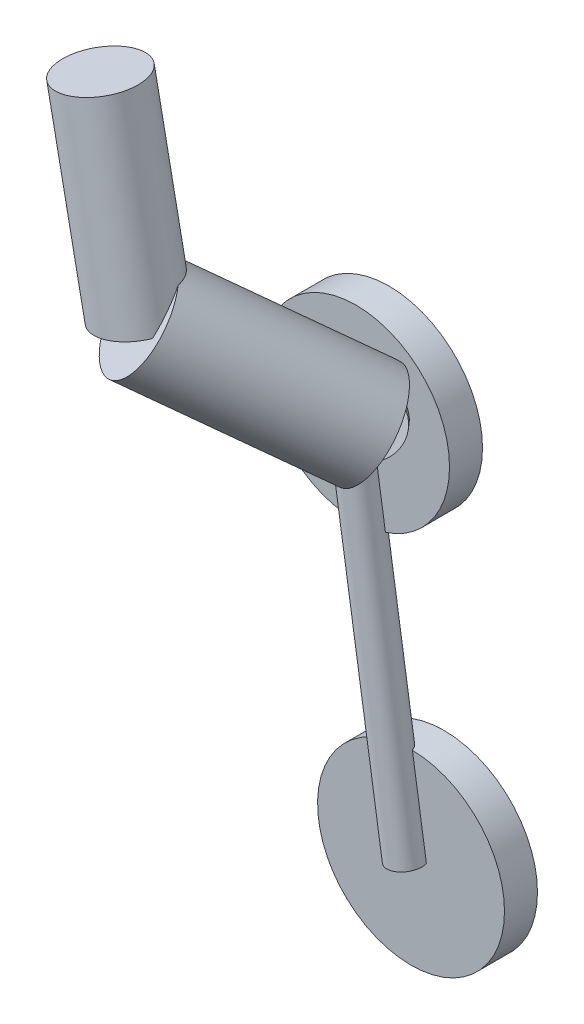
SolidWorks part; units mm, degrees
ref_plane "Alzado" through (0, 0, 0) normal (0, 0, 1) x (1, 0, 0)
ref_plane "Planta" through (0, 0, 0) normal (0, 1, 0) x (1, 0, 0)
ref_plane "Vista lateral" through (0, 0, 0) normal (1, 0, 0) x (0, 0, -1)
sketch3d "Sk_Patilla"
  line L0 (-425.1, 65, 76) -> (-418.1, 30, 76)
  dimension "D1" = 35.6931
sweep "Patilla" add path "Sk_Patilla" circular profile diameter 14 parameters "D3"=14
sketch3d "Sk_Paralelogramo"
  line L0 (-418.1, 30, 76) -> (-400.1, 10, 52)
  dimension "D1" = 36.0555
sweep "Paralelogramo" add path "Sk_Paralelogramo" circular profile diameter 18 parameters "D3"=18
sketch3d "Sk_Union_jaula"
  line L0 (-400.1, 10, 52) -> (-408.1, 5, 43.5)
  dimension "D1" = 12.6984
sweep "Union_jaula" add path "Sk_Union_jaula" circular profile diameter 10 parameters "D3"=10
sketch3d "Sk_Jaula"
  line L0 (-408.1, 5, 47.5) -> (-398.1, -60, 47.5)
  dimension "D1" = 65.7647
sweep "Jaula" add path "Sk_Jaula" circular profile diameter 6 parameters "D3"=6
sketch3d "Sk_Polea_superior"
  line L0 (-408.1, 5, 40.5) -> (-408.1, 5, 46.5)
sweep "Polea_superior" add path "Sk_Polea_superior" circular profile diameter 34 parameters "D3"=34
sketch3d "Sk_Polea_inferior"
  line L0 (-398.1, -60, 40.5) -> (-398.1, -60, 46.5)
sweep "Polea_inferior" add path "Sk_Polea_inferior" circular profile diameter 34 parameters "D3"=34
